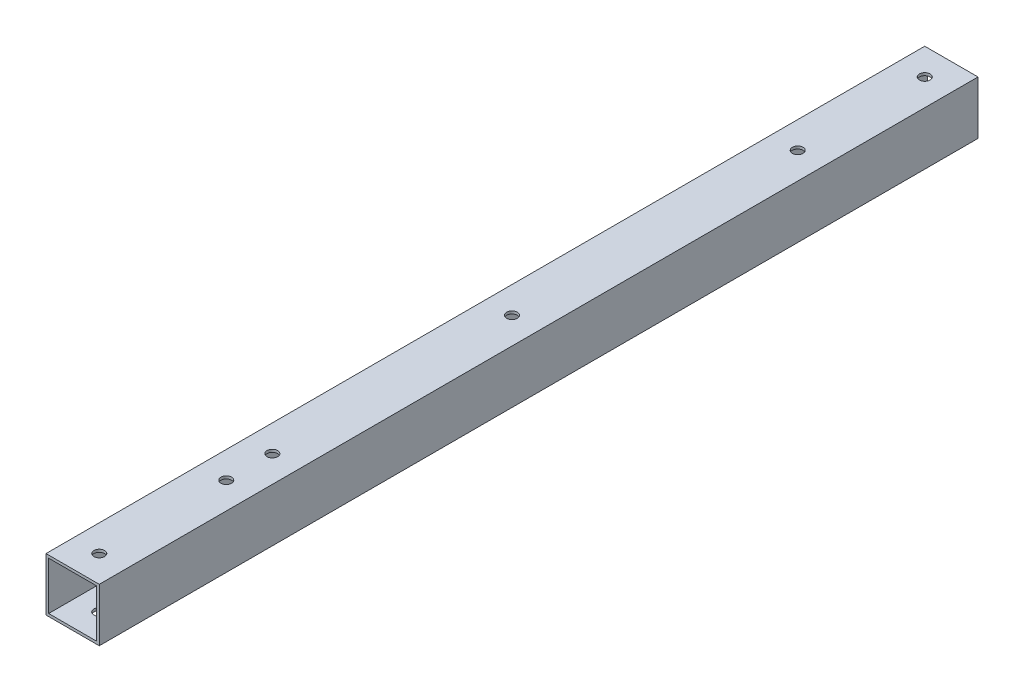
SolidWorks part; units mm, degrees
ref_plane "前视基准面" through (0, 0, 0) normal (0, 0, 1) x (1, 0, 0)
ref_plane "上视基准面" through (0, 0, 0) normal (0, 1, 0) x (1, 0, 0)
ref_plane "右视基准面" through (0, 0, 0) normal (1, 0, 0) x (0, 0, -1)
sketch "草图1" plane through (0, 0, 0) normal (0, 0, 1) x (1, 0, 0)
  line L1 (-10, 10) -> (10, 10)
  line L2 (-10, 10) -> (-10, -10)
  line L3 (-10, -10) -> (10, -10)
  line L4 (10, 10) -> (10, -10)
  line L5 (-10, 10) -> (10, -10) construction
  line L6 (-10, -10) -> (10, 10) construction
  line L7 (-9, 9) -> (9, 9)
  line L8 (-9, 9) -> (-9, -9)
  line L9 (-9, -9) -> (9, -9)
  line L10 (9, 9) -> (9, -9)
  line L11 (-9, 9) -> (9, -9) construction
  line L12 (-9, -9) -> (9, 9) construction
  point P0 (0, 0)
  point P6 (0, 0)
extrude "凸台-拉伸1" add sketch "草图1" along normal mid plane 330
ref_plane "基准面1" through (0, 0, 0) normal (0, 0, 1) x (1, 0, 0)
hole_wizard "大小mm 暗销孔1" positions "草图3" profile "草图2" hole size "Ø4.0" standard "GB" end condition through all
sketch "草图3" plane through (0, -10, 0) normal (0, -1, 0) x (-1, 0, 0)
  line L0 (0, 0) -> (0, -107.3)
  point P0 (0, -107.3)
sketch "草图2" plane through (0, -10, 107.3) normal (1, 0, 0) x (0, 0, -1)
  line L0 (0, 0) -> (0, 20)
  line L1 (0, 20) -> (2, 20)
  line L2 (2, 20) -> (2, 0)
  line L5 (2, 0) -> (0, 0)
  line L11 (0, -6.35) -> (0, 107.95) construction
  dimension "通孔孔直径" = 4
  dimension "通孔孔深度" = 20
mirror "镜向1" about plane through (0, 0, 0) normal (0, 0, 1) of "大小mm 暗销孔1"
hole_wizard "Ø4.0 (4) 直径孔1" positions "草图5" profile "草图4" hole size "Ø4.0" standard "GB" end condition through all
sketch "草图5" plane through (0, -10, 0) normal (0, -1, 0) x (-1, 0, 0)
  line L0 (0, 0) -> (0, -155)
  line L2 (0, -155) -> (0, -165)
  line L3 (10, -165) -> (-10, -165) construction
  point P0 (0, -155)
sketch "草图4" plane through (0, -10, 155) normal (1, 0, 0) x (0, 0, -1)
  line L0 (0, 0) -> (0, 20)
  line L1 (0, 20) -> (2, 20)
  line L2 (2, 20) -> (2, 0)
  line L5 (2, 0) -> (0, 0)
  line L11 (0, -6.35) -> (0, 107.95) construction
  dimension "通孔孔直径" = 4
  dimension "通孔孔深度" = 20
mirror "镜向2" about plane through (0, 0, 0) normal (0, 0, 1) of "Ø4.0 (4) 直径孔1"
hole_wizard "Ø4.0 (4) 直径孔2" positions "草图7" profile "草图6" hole size "Ø4.0" standard "GB" end condition through all
sketch "草图7" plane through (0, -10, 0) normal (0, -1, 0) x (-1, 0, 0)
  line L0 (0, -90) -> (0, -165)
  line L1 (10, -165) -> (-10, -165) construction
  line L2 (0, -165) -> (0, 0)
  point P0 (0, -90)
  point P13 (0, 0)
sketch "草图6" plane through (0, -10, 90) normal (1, 0, 0) x (0, 0, -1)
  line L0 (0, 0) -> (0, 20)
  line L1 (0, 20) -> (2, 20)
  line L2 (2, 20) -> (2, 0)
  line L5 (2, 0) -> (0, 0)
  line L11 (0, -6.35) -> (0, 107.95) construction
  dimension "通孔孔直径" = 4
  dimension "通孔孔深度" = 20
